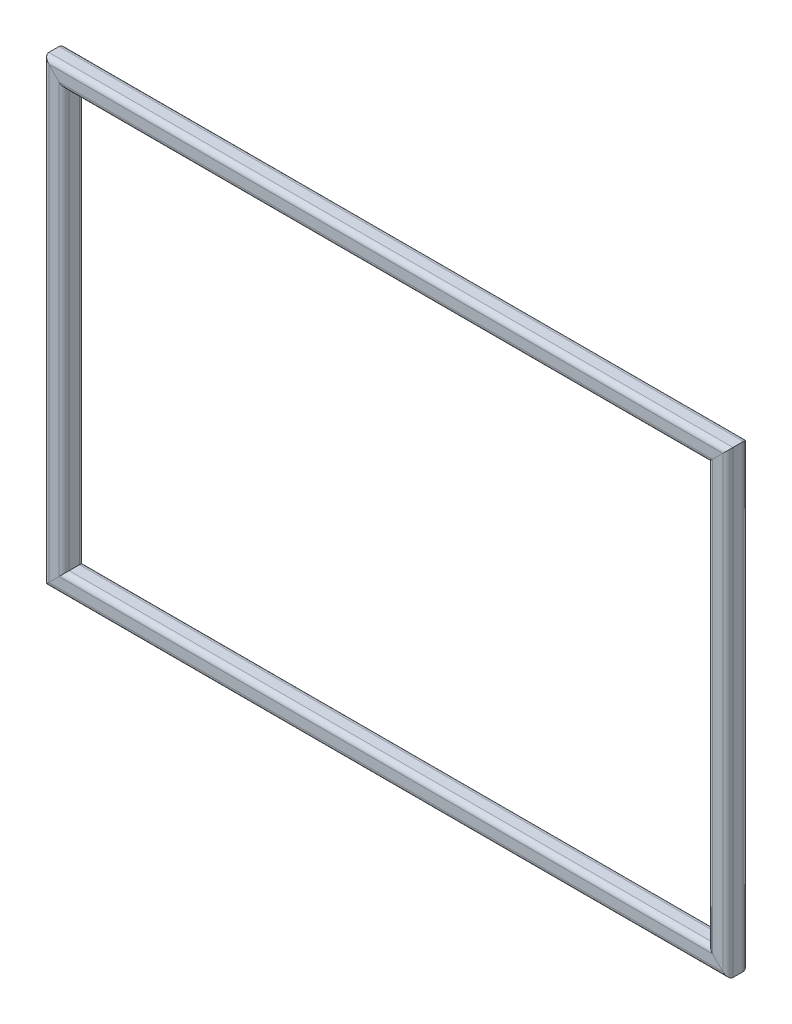
SolidWorks part; units mm, degrees
ref_plane "Alzado" through (0, 0, 0) normal (0, 0, 1) x (1, 0, 0)
ref_plane "Planta" through (0, 0, 0) normal (0, 1, 0) x (1, 0, 0)
ref_plane "Vista lateral" through (0, 0, 0) normal (1, 0, 0) x (0, 0, -1)
sketch "Croquis1" plane through (0, 0, 0) normal (0, 0, 1) x (1, 0, 0)
  line L1 (-400, 260) -> (400, 260)
  line L2 (-400, 260) -> (-400, -260)
  line L3 (-400, -260) -> (400, -260)
  line L4 (400, 260) -> (400, -260)
  line L5 (-400, 260) -> (400, -260) construction
  line L6 (-400, -260) -> (400, 260) construction
  point P0 (0, 0)
  dimension "D1" = 800
  dimension "D2" = 520
other "Tubo cuadrado 2 X 2 X 0.25(1)"
ref_plane "Plano1" through (-412.7, 260, 12.7) normal (0, -1, 0) x (1, 0, 0)
sketch "Sketch1" plane through (-412.7, 260, 12.7) normal (0, -1, 0) x (1, 0, 0)
  line L0 (-6.35, -9.525) -> (6.35, -9.525)
  line L1 (-9.525, -6.35) -> (-9.525, 6.35)
  line L2 (6.35, 9.525) -> (-6.35, 9.525)
  line L3 (9.525, 6.35) -> (9.525, -6.35)
  line L4 (-6.35, -12.7) -> (6.35, -12.7)
  line L5 (-12.7, -6.35) -> (-12.7, 6.35)
  line L6 (6.35, 12.7) -> (-6.35, 12.7)
  line L7 (12.7, 6.35) -> (12.7, -6.35)
  line L8 (0, 0) -> (9.525, 0) construction
  line L9 (0, 0) -> (0, 9.525) construction
  arc A0 (12.7, 6.35) -> (6.35, 12.7) centre (6.35, 6.35) ccw
  arc A1 (6.35, -12.7) -> (12.7, -6.35) centre (6.35, -6.35) ccw
  arc A2 (-12.7, -6.35) -> (-6.35, -12.7) centre (-6.35, -6.35) ccw
  arc A3 (-6.35, 12.7) -> (-12.7, 6.35) centre (-6.35, 6.35) ccw
  arc A4 (-6.35, 9.525) -> (-9.525, 6.35) centre (-6.35, 6.35) ccw
  arc A5 (9.525, 6.35) -> (6.35, 9.525) centre (6.35, 6.35) ccw
  arc A6 (6.35, -9.525) -> (9.525, -6.35) centre (6.35, -6.35) ccw
  arc A7 (-9.525, -6.35) -> (-6.35, -9.525) centre (-6.35, -6.35) ccw
  point P3 (0, 12.7)
  point P4 (12.7, 0)
  point P5 (0, -12.7)
  point P6 (-12.7, 0)
  point P7 (-12.7, 12.7)
  point P8 (-12.7, -12.7)
  point P33 (0, 0)
  point P35 (12.7, -12.7)
  point P36 (12.7, 12.7)
  point P37 (0, 0)
  dimension "D1" = 6.35
  dimension "Thickness" = 3.175
  dimension "V_leg" = 25.4
